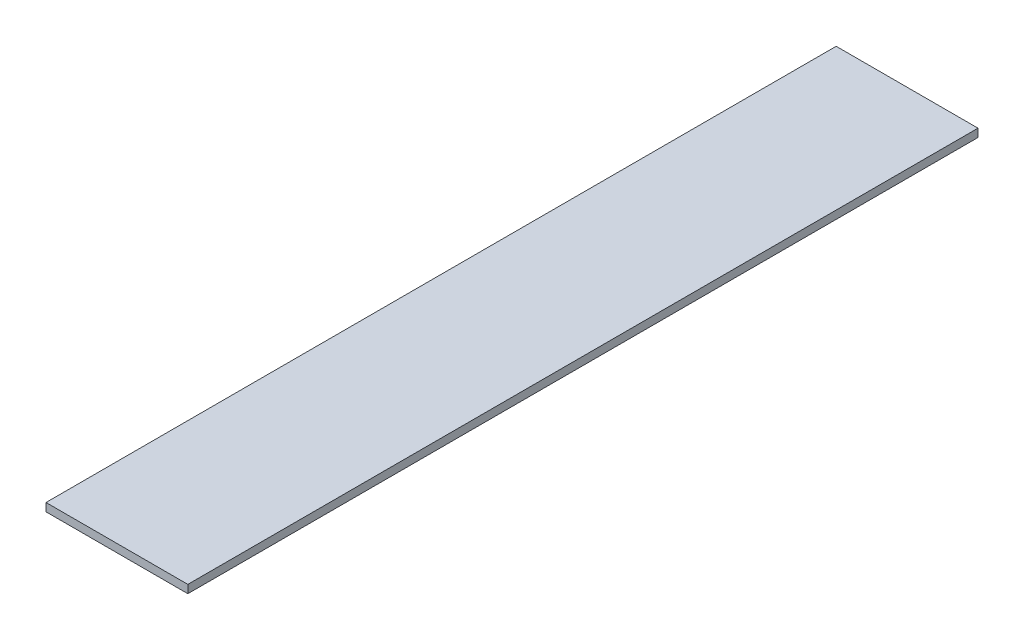
SolidWorks part; units mm, degrees
ref_plane "Front Plane" through (0, 0, 0) normal (0, 0, 1) x (1, 0, 0)
ref_plane "Top Plane" through (0, 0, 0) normal (0, 1, 0) x (1, 0, 0)
ref_plane "Right Plane" through (0, 0, 0) normal (1, 0, 0) x (0, 0, -1)
sketch "Sketch1" plane through (0, 0, 0) normal (0, 1, 0) x (1, 0, 0)
  line L1 (0, 0) -> (35, 0)
  line L2 (0, 0) -> (0, 195)
  line L3 (0, 195) -> (35, 195)
  line L4 (35, 0) -> (35, 195)
  dimension "D1" = 195
  dimension "D2" = 35
extrude "Boss-Extrude1" add sketch "Sketch1" along normal blind 2
